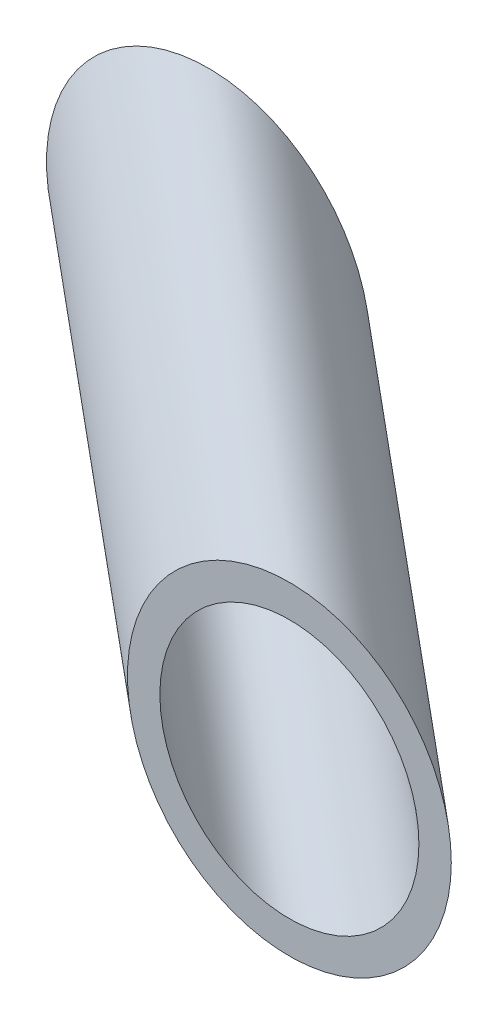
SolidWorks part; units mm, degrees
material "Copper"
ref_plane "Front Plane" through (0, 0, 0) normal (0, 0, 1) x (1, 0, 0)
ref_plane "Top Plane" through (0, 0, 0) normal (0, 1, 0) x (1, 0, 0)
ref_plane "Right Plane" through (0, 0, 0) normal (1, 0, 0) x (0, 0, -1)
sketch "Sketch1" plane through (0, 0, 0) normal (0, 0, 1) x (1, 0, 0)
  circle A0 centre (0, 0) radius 12.7
  circle A1 centre (0, 0) radius 10.16
  dimension "D1" = 20.32
  dimension "D2" = 25.4
sketch "Sketch2" plane through (0, 0, 0) normal (0, 1, 0) x (1, 0, 0)
  line L0 (0, 0) -> (38.1, -31.75)
  dimension "D1" = 31.75
  dimension "D2" = 38.1
sweep "Sweep1" add profiles "Sketch1" path "Sketch2"
